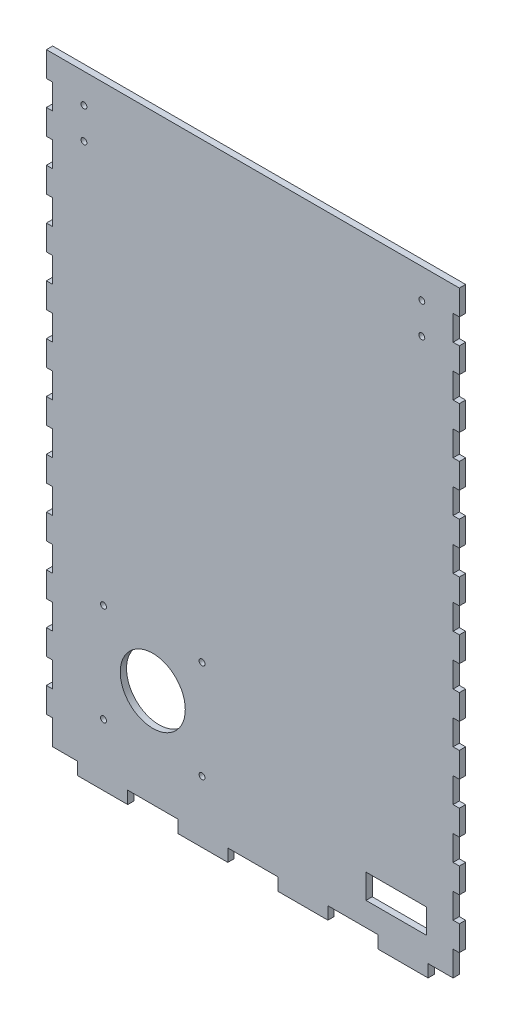
SolidWorks part; units mm, degrees
ref_plane "Front Plane" through (0, 0, 0) normal (0, 0, 1) x (1, 0, 0)
ref_plane "Top Plane" through (0, 0, 0) normal (0, 1, 0) x (1, 0, 0)
ref_plane "Right Plane" through (0, 0, 0) normal (1, 0, 0) x (0, 0, -1)
sketch "Sketch1" plane through (0, 0, 0) normal (0, 0, 1) x (1, 0, 0)
  line L0 (0, 0) -> (203.2, 0)
  line L1 (203.2, 0) -> (203.2, 304.8)
  line L2 (203.2, 304.8) -> (0, 304.8)
  line L3 (0, 304.8) -> (0, 0)
  dimension "D1" = 203.2
  dimension "D2" = 304.8
extrude "Boss-Extrude1" add sketch "Sketch1" along normal blind 3.175
sketch "Sketch2" plane through (0, 0, 3.175) normal (0, 0, 1) x (1, 0, 0)
  line L0 (0, 304.8) -> (-3.175, 304.8)
  line L1 (-3.175, 304.8) -> (-3.175, 292.1)
  line L2 (-3.175, 292.1) -> (0, 292.1)
  line L3 (0, 304.8) -> (0, 0) construction
  line L4 (0, 292.1) -> (0, 304.8)
  line L5 (101.6, 304.8) -> (101.6, 0) construction
  line L6 (203.2, 304.8) -> (0, 304.8) construction
  line L7 (0, 0) -> (203.2, 0) construction
  line L8 (206.375, 292.1) -> (203.2, 292.1)
  line L9 (206.375, 304.8) -> (206.375, 292.1)
  line L10 (203.2, 304.8) -> (206.375, 304.8)
  line L11 (203.2, 292.1) -> (203.2, 304.8)
  line L12 (0, 266.7) -> (0, 279.4)
  line L13 (0, 279.4) -> (-3.175, 279.4)
  line L14 (-3.175, 279.4) -> (-3.175, 266.7)
  line L15 (-3.175, 266.7) -> (0, 266.7)
  line L16 (206.375, 266.7) -> (203.2, 266.7)
  line L17 (203.2, 266.7) -> (203.2, 279.4)
  line L18 (203.2, 279.4) -> (206.375, 279.4)
  line L19 (206.375, 279.4) -> (206.375, 266.7)
  line L20 (0, 241.3) -> (0, 254)
  line L21 (0, 254) -> (-3.175, 254)
  line L22 (-3.175, 254) -> (-3.175, 241.3)
  line L23 (-3.175, 241.3) -> (0, 241.3)
  line L24 (206.375, 241.3) -> (203.2, 241.3)
  line L25 (203.2, 241.3) -> (203.2, 254)
  line L26 (203.2, 254) -> (206.375, 254)
  line L27 (206.375, 254) -> (206.375, 241.3)
  line L28 (0, 215.9) -> (0, 228.6)
  line L29 (0, 228.6) -> (-3.175, 228.6)
  line L30 (-3.175, 228.6) -> (-3.175, 215.9)
  line L31 (-3.175, 215.9) -> (0, 215.9)
  line L32 (206.375, 215.9) -> (203.2, 215.9)
  line L33 (203.2, 215.9) -> (203.2, 228.6)
  line L34 (203.2, 228.6) -> (206.375, 228.6)
  line L35 (206.375, 228.6) -> (206.375, 215.9)
  line L36 (0, 190.5) -> (0, 203.2)
  line L37 (0, 203.2) -> (-3.175, 203.2)
  line L38 (-3.175, 203.2) -> (-3.175, 190.5)
  line L39 (-3.175, 190.5) -> (0, 190.5)
  line L40 (206.375, 190.5) -> (203.2, 190.5)
  line L41 (203.2, 190.5) -> (203.2, 203.2)
  line L42 (203.2, 203.2) -> (206.375, 203.2)
  line L43 (206.375, 203.2) -> (206.375, 190.5)
  line L44 (0, 165.1) -> (0, 177.8)
  line L45 (0, 177.8) -> (-3.175, 177.8)
  line L46 (-3.175, 177.8) -> (-3.175, 165.1)
  line L47 (-3.175, 165.1) -> (0, 165.1)
  line L48 (206.375, 165.1) -> (203.2, 165.1)
  line L49 (203.2, 165.1) -> (203.2, 177.8)
  line L50 (203.2, 177.8) -> (206.375, 177.8)
  line L51 (206.375, 177.8) -> (206.375, 165.1)
  line L52 (0, 139.7) -> (0, 152.4)
  line L53 (0, 152.4) -> (-3.175, 152.4)
  line L54 (-3.175, 152.4) -> (-3.175, 139.7)
  line L55 (-3.175, 139.7) -> (0, 139.7)
  line L56 (206.375, 139.7) -> (203.2, 139.7)
  line L57 (203.2, 139.7) -> (203.2, 152.4)
  line L58 (203.2, 152.4) -> (206.375, 152.4)
  line L59 (206.375, 152.4) -> (206.375, 139.7)
  line L60 (0, 114.3) -> (0, 127)
  line L61 (0, 127) -> (-3.175, 127)
  line L62 (-3.175, 127) -> (-3.175, 114.3)
  line L63 (-3.175, 114.3) -> (0, 114.3)
  line L64 (206.375, 114.3) -> (203.2, 114.3)
  line L65 (203.2, 114.3) -> (203.2, 127)
  line L66 (203.2, 127) -> (206.375, 127)
  line L67 (206.375, 127) -> (206.375, 114.3)
  line L68 (0, 88.9) -> (0, 101.6)
  line L69 (0, 101.6) -> (-3.175, 101.6)
  line L70 (-3.175, 101.6) -> (-3.175, 88.9)
  line L71 (-3.175, 88.9) -> (0, 88.9)
  line L72 (206.375, 88.9) -> (203.2, 88.9)
  line L73 (203.2, 88.9) -> (203.2, 101.6)
  line L74 (203.2, 101.6) -> (206.375, 101.6)
  line L75 (206.375, 101.6) -> (206.375, 88.9)
  line L76 (0, 63.5) -> (0, 76.2)
  line L77 (0, 76.2) -> (-3.175, 76.2)
  line L78 (-3.175, 76.2) -> (-3.175, 63.5)
  line L79 (-3.175, 63.5) -> (0, 63.5)
  line L80 (206.375, 63.5) -> (203.2, 63.5)
  line L81 (203.2, 63.5) -> (203.2, 76.2)
  line L82 (203.2, 76.2) -> (206.375, 76.2)
  line L83 (206.375, 76.2) -> (206.375, 63.5)
  line L84 (0, 38.1) -> (0, 50.8)
  line L85 (0, 50.8) -> (-3.175, 50.8)
  line L86 (-3.175, 50.8) -> (-3.175, 38.1)
  line L87 (-3.175, 38.1) -> (0, 38.1)
  line L88 (206.375, 38.1) -> (203.2, 38.1)
  line L89 (203.2, 38.1) -> (203.2, 50.8)
  line L90 (203.2, 50.8) -> (206.375, 50.8)
  line L91 (206.375, 50.8) -> (206.375, 38.1)
  line L92 (0, 12.7) -> (0, 25.4)
  line L93 (0, 25.4) -> (-3.175, 25.4)
  line L94 (-3.175, 25.4) -> (-3.175, 12.7)
  line L95 (-3.175, 12.7) -> (0, 12.7)
  line L96 (206.375, 12.7) -> (203.2, 12.7)
  line L97 (203.2, 12.7) -> (203.2, 25.4)
  line L98 (203.2, 25.4) -> (206.375, 25.4)
  line L99 (206.375, 25.4) -> (206.375, 12.7)
  line L100 (0, 292.1) -> (0, 266.7) construction
  line L101 (12.7, 0) -> (12.7, -6.35)
  line L102 (12.7, -6.35) -> (38.1, -6.35)
  line L103 (38.1, -6.35) -> (38.1, 0)
  line L104 (38.1, 0) -> (12.7, 0)
  line L105 (88.9, 0) -> (63.5, 0)
  line L106 (63.5, 0) -> (63.5, -6.35)
  line L107 (63.5, -6.35) -> (88.9, -6.35)
  line L108 (88.9, -6.35) -> (88.9, 0)
  line L109 (139.7, 0) -> (114.3, 0)
  line L110 (114.3, 0) -> (114.3, -6.35)
  line L111 (114.3, -6.35) -> (139.7, -6.35)
  line L112 (139.7, -6.35) -> (139.7, 0)
  line L113 (190.5, 0) -> (165.1, 0)
  line L114 (165.1, 0) -> (165.1, -6.35)
  line L115 (165.1, -6.35) -> (190.5, -6.35)
  line L116 (190.5, -6.35) -> (190.5, 0)
  line L117 (38.1, 0) -> (88.9, 0) construction
  dimension "D1" = 3.175
  dimension "D2" = 12.7
  dimension "D4" = 25.4
  dimension "D5" = 12.7
  dimension "D6" = 6.35
  dimension "D7" = 25.4
  dimension "D9" = 50.8
  dimension "D3" = 12
  dimension "D8" = 4
extrude "Boss-Extrude2" add sketch "Sketch2" against normal up to surface (3.175 mm away) up to face at (101.6, 152.4, 0)
sketch "Sketch3" [suppressed] plane through (0, 0, 3.175) normal (0, 0, 1) x (1, 0, 0)
  line L0 (0, 0) -> (-3.175, 0)
  line L1 (-3.175, 0) -> (-3.175, 12.7)
  line L2 (-3.175, 12.7) -> (0, 12.7)
  line L3 (0, 304.8) -> (0, 0) construction
  line L4 (0, 12.7) -> (0, 0)
  line L5 (101.6, 304.8) -> (101.6, 0) construction
  line L6 (203.2, 304.8) -> (0, 304.8) construction
  line L7 (0, 0) -> (203.2, 0) construction
  line L8 (206.375, 12.7) -> (203.2, 12.7)
  line L9 (206.375, 0) -> (206.375, 12.7)
  line L10 (203.2, 0) -> (206.375, 0)
  line L11 (203.2, 12.7) -> (203.2, 0)
  line L12 (0, 38.1) -> (0, 25.4)
  line L13 (0, 25.4) -> (-3.175, 25.4)
  line L14 (-3.175, 25.4) -> (-3.175, 38.1)
  line L15 (-3.175, 38.1) -> (0, 38.1)
  line L16 (206.375, 38.1) -> (203.2, 38.1)
  line L17 (203.2, 38.1) -> (203.2, 25.4)
  line L18 (203.2, 25.4) -> (206.375, 25.4)
  line L19 (206.375, 25.4) -> (206.375, 38.1)
  line L20 (0, 63.5) -> (0, 50.8)
  line L21 (0, 50.8) -> (-3.175, 50.8)
  line L22 (-3.175, 50.8) -> (-3.175, 63.5)
  line L23 (-3.175, 63.5) -> (0, 63.5)
  line L24 (206.375, 63.5) -> (203.2, 63.5)
  line L25 (203.2, 63.5) -> (203.2, 50.8)
  line L26 (203.2, 50.8) -> (206.375, 50.8)
  line L27 (206.375, 50.8) -> (206.375, 63.5)
  line L28 (0, 88.9) -> (0, 76.2)
  line L29 (0, 76.2) -> (-3.175, 76.2)
  line L30 (-3.175, 76.2) -> (-3.175, 88.9)
  line L31 (-3.175, 88.9) -> (0, 88.9)
  line L32 (206.375, 88.9) -> (203.2, 88.9)
  line L33 (203.2, 88.9) -> (203.2, 76.2)
  line L34 (203.2, 76.2) -> (206.375, 76.2)
  line L35 (206.375, 76.2) -> (206.375, 88.9)
  line L36 (0, 114.3) -> (0, 101.6)
  line L37 (0, 101.6) -> (-3.175, 101.6)
  line L38 (-3.175, 101.6) -> (-3.175, 114.3)
  line L39 (-3.175, 114.3) -> (0, 114.3)
  line L40 (206.375, 114.3) -> (203.2, 114.3)
  line L41 (203.2, 114.3) -> (203.2, 101.6)
  line L42 (203.2, 101.6) -> (206.375, 101.6)
  line L43 (206.375, 101.6) -> (206.375, 114.3)
  line L44 (0, 139.7) -> (0, 127)
  line L45 (0, 127) -> (-3.175, 127)
  line L46 (-3.175, 127) -> (-3.175, 139.7)
  line L47 (-3.175, 139.7) -> (0, 139.7)
  line L48 (206.375, 139.7) -> (203.2, 139.7)
  line L49 (203.2, 139.7) -> (203.2, 127)
  line L50 (203.2, 127) -> (206.375, 127)
  line L51 (206.375, 127) -> (206.375, 139.7)
  line L52 (0, 165.1) -> (0, 152.4)
  line L53 (0, 152.4) -> (-3.175, 152.4)
  line L54 (-3.175, 152.4) -> (-3.175, 165.1)
  line L55 (-3.175, 165.1) -> (0, 165.1)
  line L56 (206.375, 165.1) -> (203.2, 165.1)
  line L57 (203.2, 165.1) -> (203.2, 152.4)
  line L58 (203.2, 152.4) -> (206.375, 152.4)
  line L59 (206.375, 152.4) -> (206.375, 165.1)
  line L60 (0, 190.5) -> (0, 177.8)
  line L61 (0, 177.8) -> (-3.175, 177.8)
  line L62 (-3.175, 177.8) -> (-3.175, 190.5)
  line L63 (-3.175, 190.5) -> (0, 190.5)
  line L64 (206.375, 190.5) -> (203.2, 190.5)
  line L65 (203.2, 190.5) -> (203.2, 177.8)
  line L66 (203.2, 177.8) -> (206.375, 177.8)
  line L67 (206.375, 177.8) -> (206.375, 190.5)
  line L68 (0, 215.9) -> (0, 203.2)
  line L69 (0, 203.2) -> (-3.175, 203.2)
  line L70 (-3.175, 203.2) -> (-3.175, 215.9)
  line L71 (-3.175, 215.9) -> (0, 215.9)
  line L72 (206.375, 215.9) -> (203.2, 215.9)
  line L73 (203.2, 215.9) -> (203.2, 203.2)
  line L74 (203.2, 203.2) -> (206.375, 203.2)
  line L75 (206.375, 203.2) -> (206.375, 215.9)
  line L76 (0, 241.3) -> (0, 228.6)
  line L77 (0, 228.6) -> (-3.175, 228.6)
  line L78 (-3.175, 228.6) -> (-3.175, 241.3)
  line L79 (-3.175, 241.3) -> (0, 241.3)
  line L80 (206.375, 241.3) -> (203.2, 241.3)
  line L81 (203.2, 241.3) -> (203.2, 228.6)
  line L82 (203.2, 228.6) -> (206.375, 228.6)
  line L83 (206.375, 228.6) -> (206.375, 241.3)
  line L84 (0, 266.7) -> (0, 254)
  line L85 (0, 254) -> (-3.175, 254)
  line L86 (-3.175, 254) -> (-3.175, 266.7)
  line L87 (-3.175, 266.7) -> (0, 266.7)
  line L88 (206.375, 266.7) -> (203.2, 266.7)
  line L89 (203.2, 266.7) -> (203.2, 254)
  line L90 (203.2, 254) -> (206.375, 254)
  line L91 (206.375, 254) -> (206.375, 266.7)
  line L92 (0, 292.1) -> (0, 279.4)
  line L93 (0, 279.4) -> (-3.175, 279.4)
  line L94 (-3.175, 279.4) -> (-3.175, 292.1)
  line L95 (-3.175, 292.1) -> (0, 292.1)
  line L96 (206.375, 292.1) -> (203.2, 292.1)
  line L97 (203.2, 292.1) -> (203.2, 279.4)
  line L98 (203.2, 279.4) -> (206.375, 279.4)
  line L99 (206.375, 279.4) -> (206.375, 292.1)
  line L100 (0, 12.7) -> (0, 38.1) construction
  line L101 (12.7, 0) -> (12.7, -6.35)
  line L102 (12.7, -6.35) -> (38.1, -6.35)
  line L103 (38.1, -6.35) -> (38.1, 0)
  line L104 (38.1, 0) -> (12.7, 0)
  line L105 (88.9, 0) -> (63.5, 0)
  line L106 (63.5, 0) -> (63.5, -6.35)
  line L107 (63.5, -6.35) -> (88.9, -6.35)
  line L108 (88.9, -6.35) -> (88.9, 0)
  line L109 (139.7, 0) -> (114.3, 0)
  line L110 (114.3, 0) -> (114.3, -6.35)
  line L111 (114.3, -6.35) -> (139.7, -6.35)
  line L112 (139.7, -6.35) -> (139.7, 0)
  line L113 (190.5, 0) -> (165.1, 0)
  line L114 (165.1, 0) -> (165.1, -6.35)
  line L115 (165.1, -6.35) -> (190.5, -6.35)
  line L116 (190.5, -6.35) -> (190.5, 0)
  line L117 (38.1, 0) -> (88.9, 0) construction
  dimension "D1" = 3.175
  dimension "D2" = 12.7
  dimension "D9" = 50.8
  dimension "D3" = 12
  dimension "D8" = 4
  dimension "D4" = 25.4
  dimension "D5" = 6.35
  dimension "D6" = 25.4
  dimension "D7" = 12.7
sketch "Sketch4" plane through (0, 0, 3.175) normal (0, 0, 1) x (1, 0, 0)
  line L0 (50.8, 33.5) -> (50.8, 66.5) construction
  line L1 (34.3, 50) -> (67.3, 50) construction
  line L2 (0, 12.7) -> (0, 0) construction
  line L3 (88.9, 0) -> (114.3, 0) construction
  circle A0 centre (50.8, 50) radius 16.5
  circle A1 centre (25.8, 75) radius 1.5
  circle A5 centre (75.8, 75) radius 1.5
  circle A6 centre (75.8, 25) radius 1.5
  circle A7 centre (25.8, 25) radius 1.5
  dimension "D5" = 33
  dimension "D6" = 3
  dimension "D1" = 50
  dimension "D2" = 50
  dimension "D3" = 50.8
  dimension "D4" = 50
extrude "Cut-Extrude1" cut sketch "Sketch4" against normal up to surface (3.175 mm away) up to face at (101.6, 130.175, 0)
sketch "Sketch5" plane through (0, 0, 0) normal (0, 0, -1) x (-1, 0, 0)
  line L1 (-206.375, 304.8) -> (-206.375, 292.1) construction
  line L2 (-206.375, 304.8) -> (3.175, 304.8) construction
  line L3 (-101.6, 304.8) -> (-101.6, 0) construction
  line L4 (-88.9, 0) -> (-114.3, 0) construction
  circle A1 centre (-187.325, 289.8) radius 1.5
  circle A2 centre (-187.325, 274.05) radius 1.5
  circle A3 centre (-15.875, 274.05) radius 1.5
  circle A4 centre (-15.875, 289.8) radius 1.5
  dimension "D1" = 3
  dimension "D2" = 3
  dimension "D3" = 15.75
  dimension "D4" = 19.05
  dimension "D5" = 15
extrude "Cut-Extrude2" cut sketch "Sketch5" against normal up to surface (3.175 mm away) up to face at (24.3, 25, 3.175)
extrude "Boss-Extrude4" [suppressed] add sketch "Sketch3" against normal up to surface (3.175 mm away)
sketch "Sketch6" [suppressed] plane through (0, 0, 0) normal (0, 0, -1) x (-1, 0, 0)
  line L1 (-203.2, 304.8) -> (0, 304.8) construction
  line L2 (-101.6, 304.8) -> (-101.6, 0) construction
  line L3 (-88.9, 0) -> (-114.3, 0) construction
  line L4 (-206.375, 292.1) -> (-206.375, 279.4) construction
  circle A0 centre (-187.325, 289.8) radius 1.5
  circle A1 centre (-187.325, 274.05) radius 1.5
  circle A2 centre (-15.875, 274.05) radius 1.5
  circle A3 centre (-15.875, 289.8) radius 1.5
  dimension "D1" = 3
  dimension "D2" = 3
  dimension "D3" = 19.05
  dimension "D4" = 15
  dimension "D5" = 15.75
extrude "Cut-Extrude3" [suppressed] cut sketch "Sketch6" against normal up to surface (3.175 mm away)
sketch "Sketch7" plane through (0, 0, 3.175) normal (0, 0, 1) x (1, 0, 0)
  line L0 (159.0125, 24.45) -> (159.0125, 12.011)
  line L1 (159.0125, 12.011) -> (189.5875, 12.011)
  line L2 (189.5875, 12.011) -> (189.5875, 24.45)
  line L3 (189.5875, 24.45) -> (159.0125, 24.45)
  line L4 (206.375, 12.7) -> (206.375, 25.4) construction
  line L5 (190.5, 0) -> (203.2, 0) construction
  dimension "D1" = 16.7875
  dimension "D2" = 24.45
  dimension "D3" = 12.439
  dimension "D4" = 30.575
extrude "Cut-Extrude4" cut sketch "Sketch7" against normal up to surface (3.175 mm away) up to face at (17.375, 289.8, 0)
equation "\"wall_thickness\"= 0.125in"
equation "\"base_thickness\"= 0.25in"
equation "\"D1@Boss-Extrude1\"=\"wall_thickness\""
equation "\"D1@Sketch2\"=\"wall_thickness\""
equation "\"D6@Sketch2\"=\"base_thickness\""
equation "\"D1@Sketch3\"=\"wall_thickness\""
equation "\"D5@Sketch3\"=\"base_thickness\""
